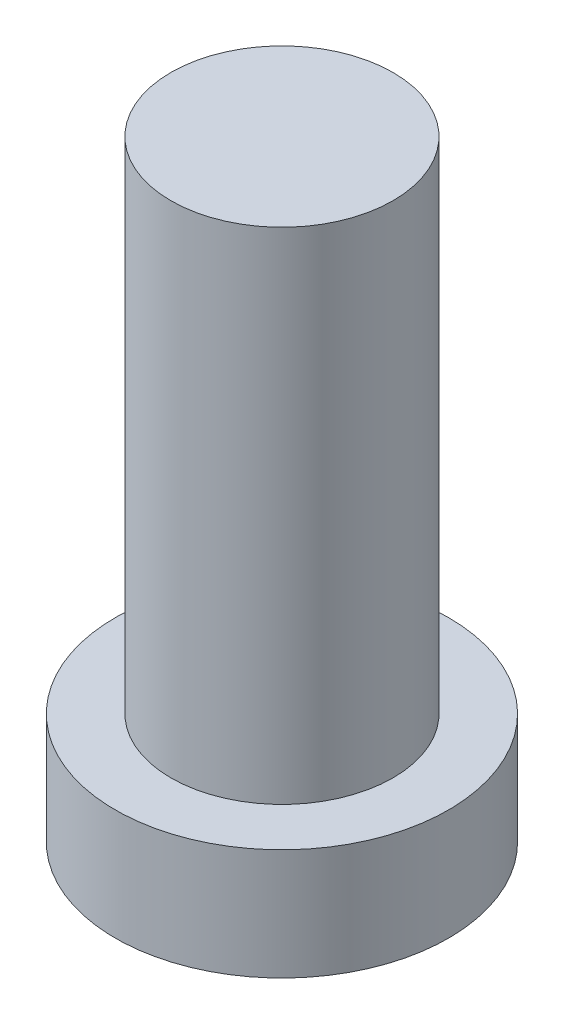
SolidWorks part; units mm, degrees
material "Chrome Stainless Steel"
ref_plane "Front" through (0, 0, 0) normal (0, 0, 1) x (1, 0, 0)
ref_plane "Top" through (0, 0, 0) normal (0, 1, 0) x (1, 0, 0)
ref_plane "Right" through (0, 0, 0) normal (1, 0, 0) x (0, 0, -1)
sketch "Sketch1" plane through (0, 0, 0) normal (0, 1, 0) x (1, 0, 0)
  circle A0 centre (0, 0) radius 2.54
  dimension "D1" = 5.08
extrude "Boss-Extrude1" add sketch "Sketch1" along normal blind 11.43
sketch "Sketch2" plane through (0, 0, 0) normal (0, -1, 0) x (1, 0, 0)
  circle A0 centre (0, 0) radius 3.81
  dimension "D1" = 7.62
extrude "Boss-Extrude2" add sketch "Sketch2" along normal blind 2.54
equation "\"D1@Boss-Extrude1\"=0.1in+0.25in+0.1in"
